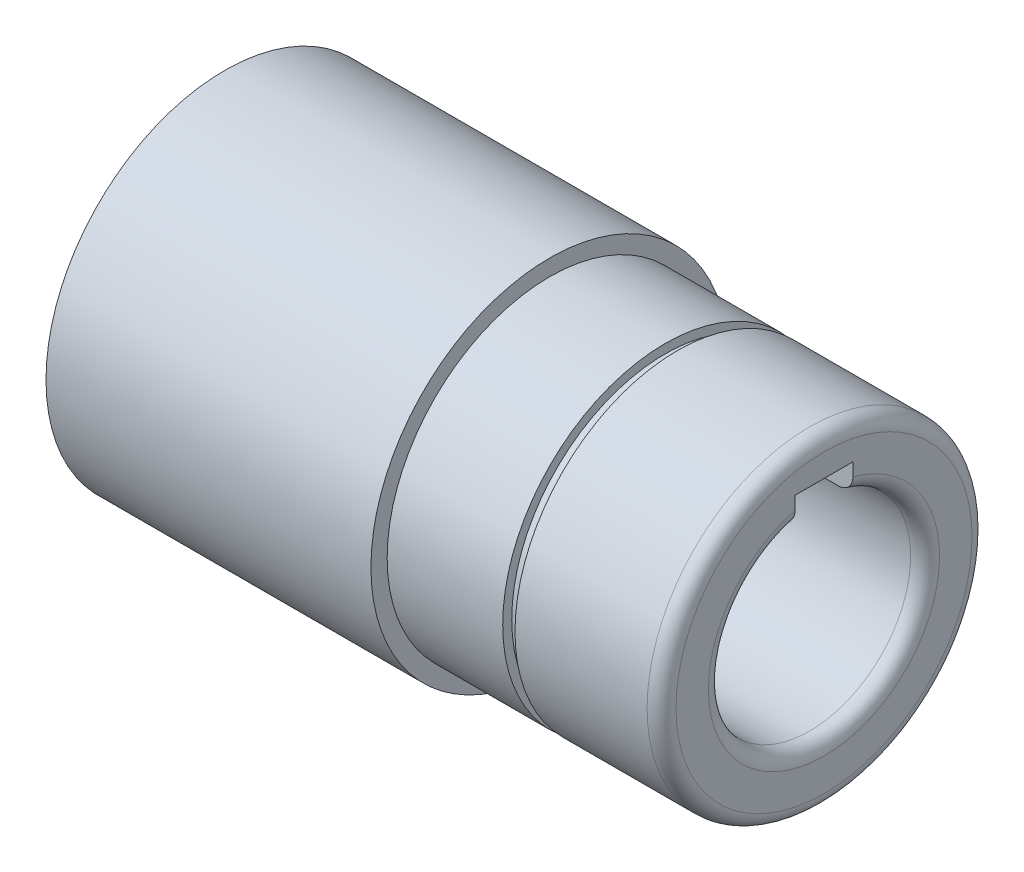
SolidWorks part; units mm, degrees
ref_plane "前视基准面" through (0, 0, 0) normal (0, 0, 1) x (1, 0, 0)
ref_plane "上视基准面" through (0, 0, 0) normal (0, 1, 0) x (1, 0, 0)
ref_plane "右视基准面" through (0, 0, 0) normal (1, 0, 0) x (0, 0, -1)
sketch "草图1" plane through (0, 0, 0) normal (0, 1, 0) x (1, 0, 0)
  line L0 (-32.6241, 0) -> (43.2624, 0) construction
  line L1 (0, 10) -> (0, 14)
  line L2 (0, 14) -> (1.5, 14)
  line L3 (1.5, 14) -> (1.5, 24.75)
  line L4 (1.5, 24.75) -> (46.5, 24.75)
  line L5 (46.5, 24.75) -> (46.5, 22.5)
  line L6 (46.5, 22.5) -> (62.5, 22.5)
  line L7 (62.5, 22.5) -> (62.5, 21.25)
  line L8 (62.5, 21.25) -> (64.2, 21.25)
  line L9 (64.2, 21.25) -> (64.2, 22.5)
  line L10 (64.2, 22.5) -> (82.5, 22.5)
  line L11 (84.5, 20.5) -> (84.5, 16)
  line L12 (82.5, 14) -> (56.5, 14)
  line L13 (56.5, 14) -> (56.5, 14.25)
  line L14 (56.5, 14.25) -> (34.5, 14.25)
  line L15 (34.5, 14.25) -> (34.5, 18)
  line L16 (34.5, 18) -> (22.5, 18)
  line L17 (22.5, 18) -> (22.5, 10)
  line L18 (22.5, 10) -> (0, 10)
  arc A0 (84.5, 20.5) -> (82.5, 22.5) centre (82.5, 20.5) ccw
  arc A1 (84.5, 16) -> (82.5, 14) centre (82.5, 16) cw
  point P5 (54.5, 22.5)
  point P26 (84.5, 14)
  dimension "D18" = 2
  dimension "D19" = 2
  dimension "D1" = 20
  dimension "D2" = 84.5
  dimension "D3" = 46.5
  dimension "D4" = 28
  dimension "D5" = 12
  dimension "D6" = 62
  dimension "D7" = 1.7
  dimension "D8" = 16
  dimension "D9" = 1.5
  dimension "D10" = 28
  dimension "D11" = 49.5
  dimension "D12" = 36
  dimension "D13" = 28.5
  dimension "D14" = 28
  dimension "D15" = 45
  dimension "D16" = 45
  dimension "D17" = 42.5
revolve "旋转1" add sketch "草图1" angle 360 about L0
sketch "草图2" plane through (0, 0, 0) normal (-1, 0, 0) x (0, 0, 1)
  line L1 (-2.5, 12.3) -> (2.5, 12.3)
  line L2 (-2.5, 12.3) -> (-2.5, 7.7)
  line L3 (-2.5, 7.7) -> (2.5, 7.7)
  line L4 (2.5, 12.3) -> (2.5, 7.7)
  line L5 (-2.5, 12.3) -> (2.5, 7.7) construction
  line L6 (-2.5, 7.7) -> (2.5, 12.3) construction
  circle A0 centre (0, 0) radius 10 construction
  point P0 (0, 10)
  dimension "D2" = 12.3
  dimension "D1" = 5
extrude "切除-拉伸1" cut sketch "草图2" against normal up to next
sketch "草图3" plane through (84.5, 0, 0) normal (1, 0, 0) x (0, 0, -1)
  line L0 (4, 14.7) -> (4, 10.8682)
  line L1 (-4, 17.3) -> (4, 17.3)
  line L2 (-4, 17.3) -> (-4, 14.7)
  line L3 (4, 10.8682) -> (-4, 10.8682)
  line L4 (4, 17.3) -> (4, 14.7)
  line L5 (-4, 17.3) -> (4, 14.7) construction
  line L6 (-4, 14.7) -> (4, 17.3) construction
  line L7 (-4, 10.8682) -> (-4, 14.7)
  circle A0 centre (0, 0) radius 16 construction
  arc A1 (-2.5, 9.6825) -> (2.5, 9.6825) centre (0, 0) ccw construction
  point P0 (0, 16)
  dimension "D1" = 8
  dimension "D2" = 17.3
extrude "切除-拉伸2" cut sketch "草图3" against normal up to next
ref_plane "基准面1" through (0, 0, 0) normal (0, 0, -1) x (-1, 0, 0)
ref_plane "面配合基准面" through (0, 0, 0) normal (-1, 0, 0) x (0, 0, 1)
